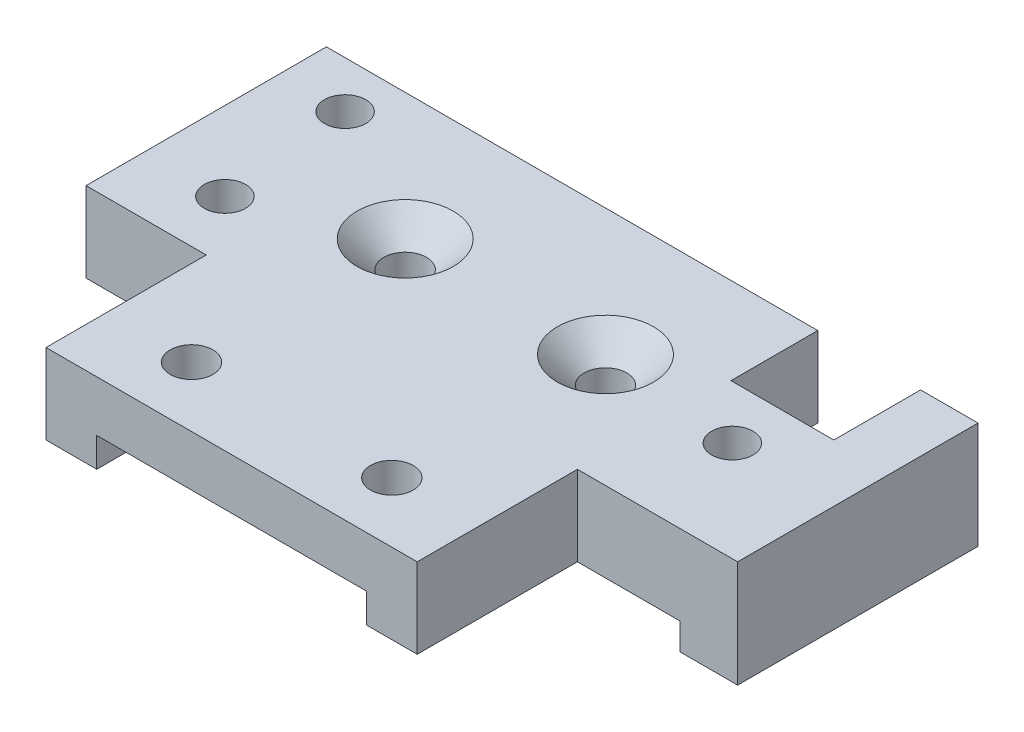
SolidWorks part; units mm, degrees
ref_plane "前视基准面" through (0, 0, 0) normal (0, 0, 1) x (1, 0, 0)
ref_plane "上视基准面" through (0, 0, 0) normal (0, 1, 0) x (1, 0, 0)
ref_plane "右视基准面" through (0, 0, 0) normal (1, 0, 0) x (0, 0, -1)
other "Configuration Table"
sketch "草图1" plane through (0, 0, 0) normal (0, 1, 0) x (1, 0, 0)
  line L1 (0, 0) -> (20.2, 0)
  line L2 (0, 0) -> (0, 25)
  line L3 (0, 25) -> (20.2, 25)
  line L4 (20.2, 0) -> (20.2, 25)
  circle A0 centre (2.6, 4.5) radius 1.6
  circle A1 centre (17.6, 4.5) radius 1.6
  circle A2 centre (17.6, 20.5) radius 1.6
  circle A3 centre (2.6, 20.5) radius 1.6
  point P7 (10.1, 0)
  point P8 (0, 12.5)
  dimension "D3" = 3.2
  dimension "D1" = 25
  dimension "D2" = 20.2
  dimension "D6" = 7.5
  dimension "D7" = 8
  dimension "D4" = 2
  dimension "D5" = 2
extrude "凸台-拉伸1" add sketch "草图1" along normal blind 3.8
sketch "草图2" plane through (20.2, 0, 0) normal (1, 0, 0) x (0, 0, -1)
  line L0 (0, 3.8) -> (25, 3.8) construction
  line L1 (25, 3.8) -> (0, 3.8)
  line L2 (25, 3.8) -> (25, -2.2)
  line L3 (25, -2.2) -> (0, -2.2)
  line L4 (0, 3.8) -> (0, -2.2)
  dimension "D1" = 6
extrude "凸台-拉伸2" add sketch "草图2" along normal blind 3.8
sketch "草图3" plane through (0, 0, 0) normal (-1, 0, 0) x (0, 0, 1)
  line L1 (-25, 3.8) -> (0, 3.8)
  line L2 (-25, 3.8) -> (-25, -2.2)
  line L3 (-25, -2.2) -> (0, -2.2)
  line L4 (0, 3.8) -> (0, -2.2)
  dimension "D1" = 6
extrude "凸台-拉伸3" add sketch "草图3" along normal blind 3.8
sketch "草图4" plane through (24, 0, 0) normal (1, 0, 0) x (0, 0, -1)
  line L0 (25, 3.8) -> (0, 3.8) construction
  line L1 (25, 3.8) -> (17, 3.8)
  line L2 (25, 3.8) -> (25, -2.2)
  line L3 (25, -2.2) -> (17, -2.2)
  line L4 (17, 3.8) -> (17, -2.2)
  line L5 (0, -2.2) -> (25, -2.2) construction
  line L6 (25, -2.2) -> (25, 3.8) construction
  dimension "D1" = 8
  dimension "D2" = 0
extrude "凸台-拉伸4" add sketch "草图4" along normal blind 12
sketch "草图5" plane through (0, 0, -25) normal (0, 0, -1) x (-1, 0, 0)
  line L0 (-36, -2.2) -> (-36, 3.8) construction
  line L1 (-36, -2.2) -> (-31.7, -2.2)
  line L2 (-36, -2.2) -> (-36, 3.8)
  line L3 (-36, 3.8) -> (-31.7, 3.8)
  line L4 (-31.7, -2.2) -> (-31.7, 3.8)
  line L5 (-36, 3.8) -> (3.8, 3.8) construction
  dimension "D1" = 4.3
extrude "凸台-拉伸5" add sketch "草图5" along normal blind 6
sketch "草图6" plane through (0, -2.2, 0) normal (0, -1, 0) x (-1, 0, 0)
  line L1 (-36, 17) -> (-31.7, 17)
  line L2 (-36, 17) -> (-36, 31)
  line L3 (-36, 31) -> (-31.7, 31)
  line L4 (-31.7, 17) -> (-31.7, 31)
extrude "凸台-拉伸6" add sketch "草图6" along normal blind 2
sketch "草图7" plane through (0, 0, -25) normal (0, 0, -1) x (-1, 0, 0)
  line L1 (3.8, 3.8) -> (0, 3.8)
  line L2 (3.8, 3.8) -> (3.8, -2.2)
  line L3 (3.8, -2.2) -> (0, -2.2)
  line L4 (0, 3.8) -> (0, -2.2)
  line L5 (-20.2, -2.2) -> (-24, -2.2)
  line L6 (-20.2, -2.2) -> (-20.2, 3.8)
  line L7 (-20.2, 3.8) -> (-24, 3.8)
  line L8 (-24, -2.2) -> (-24, 3.8)
  line L9 (-20.2, 0) -> (0, 0)
  line L10 (-20.2, 0) -> (-20.2, 3.8)
  line L11 (-20.2, 3.8) -> (0, 3.8)
  line L12 (0, 0) -> (0, 3.8)
  line M6 (-31.7, -2.2) -> (-20.2, -2.2)
  line M7 (-20.2, -2.2) -> (-20.2, 0)
  line M8 (-20.2, 0) -> (0, 0)
  line M9 (0, 0) -> (0, -2.2)
  line M10 (0, -2.2) -> (3.8, -2.2)
  line M11 (3.8, -2.2) -> (3.8, 3.8)
  line M12 (3.8, 3.8) -> (-31.7, 3.8)
extrude "凸台-拉伸7" add sketch "草图7" along normal blind 5 contours L8 L6 M6 M7 M12 | L6 L4 M8 M12 | L4 M12 M9 M10 M11
sketch "草图8" plane through (-3.8, 0, 0) normal (-1, 0, 0) x (0, 0, 1)
  line L0 (-30, -2.2) -> (-30, 3.8) construction
  line L1 (-30, 3.8) -> (-20, 3.8)
  line L2 (-30, 3.8) -> (-30, -2.2)
  line L3 (-30, -2.2) -> (-20, -2.2)
  line L4 (-20, 3.8) -> (-20, -2.2)
  line L5 (-30, -2.2) -> (0, -2.2) construction
  dimension "D1" = 0
  dimension "D2" = 10
extrude "凸台-拉伸8" add sketch "草图8" along normal blind 9
sketch "草图9" plane through (0, 3.8, 0) normal (0, 1, 0) x (1, 0, 0)
  line L0 (-3.8, 0) -> (24, 0) construction
  line L1 (-12.8, 20) -> (-3.8, 20) construction
  circle A0 centre (-7.9, 26.5) radius 1.55
  circle A1 centre (28.1, 19.5) radius 1.55
  point P6 (10.1, 0)
  dimension "D1" = 18
  dimension "D2" = 18
  dimension "D3" = 7
  dimension "D4" = 3.1
  dimension "D5" = 3.1
  dimension "D6" = 6.5
extrude "切除-拉伸1" cut sketch "草图9" against normal blind 3
sketch "草图10" plane through (0, 0.8, 0) normal (0, 1, 0) x (1, 0, 0)
  circle A0 centre (-7.9, 26.5) radius 1.05
  circle A1 centre (28.1, 19.5) radius 1.05
  dimension "D1" = 2.1
  dimension "D2" = 2.1
extrude "切除-拉伸2" cut sketch "草图10" against normal blind 3
sketch "草图11" plane through (0, 0, -20) normal (0, 0, 1) x (1, 0, 0)
  line L0 (-3.8, 3.8) -> (24, 3.8) construction
  line L1 (-3.8, 3.8) -> (-12.8, 3.8)
  line L2 (-3.8, 3.8) -> (-3.8, -2.2)
  line L3 (-3.8, -2.2) -> (-12.8, -2.2)
  line L4 (-12.8, 3.8) -> (-12.8, -2.2)
  line L5 (-3.8, -2.2) -> (-3.8, 3.8) construction
  line L6 (-12.8, -2.2) -> (-12.8, 3.8) construction
  line L7 (-12.8, -2.2) -> (-3.8, -2.2) construction
extrude "凸台-拉伸9" add sketch "草图11" along normal blind 8
sketch "草图12" plane through (0, -2.2, 0) normal (0, -1, 0) x (-1, 0, 0)
  circle A0 centre (6.9, 16.5) radius 1.05
  circle A1 centre (7.9, 26.5) radius 1.05 construction
  dimension "D1" = 2.1
  dimension "D2" = 1
  dimension "D3" = 10
extrude "切除-拉伸3" cut sketch "草图12" against normal through all
chamfer "倒角1" distance 2 angle 45 2 edges at (17.6, 3.8, -18.9) (2.6, 3.8, -18.9)
sketch "草图13" plane through (0, 3.8, 0) normal (0, 1, 0) x (1, 0, 0)
  circle A0 centre (-6.9, 16.5) radius 1.55
  dimension "D1" = 3.1
extrude "切除-拉伸4" cut sketch "草图13" against normal blind 3
sketch "草图14" plane through (0, 0, -17) normal (0, 0, 1) x (1, 0, 0)
  line L0 (24, -2.2) -> (20.2, -2.2) construction
  line L1 (24, -2.2) -> (36, -2.2)
  line L2 (24, -2.2) -> (24, 3.8)
  line L3 (24, 3.8) -> (36, 3.8)
  line L4 (36, -2.2) -> (36, 3.8)
  line L5 (31.7, -2.2) -> (24, -2.2) construction
  line L6 (36, 3.8) -> (24, 3.8) construction
  line L7 (36, 3.8) -> (36, -4.2) construction
  line L8 (36, -4.2) -> (31.7, -4.2) construction
  line L9 (31.7, -2.2) -> (36, -2.2)
  line L10 (31.7, -2.2) -> (31.7, -4.2)
  line L11 (31.7, -4.2) -> (36, -4.2)
  line L12 (36, -2.2) -> (36, -4.2)
  line M1 (24, 3.8) -> (24, -2.2)
  line M2 (24, -2.2) -> (31.7, -2.2)
  line M3 (31.7, -2.2) -> (31.7, -4.2)
  line M4 (31.7, -4.2) -> (36, -4.2)
  line M5 (36, -4.2) -> (36, 3.8)
  line M6 (36, 3.8) -> (24, 3.8)
extrude "凸台-拉伸10" add sketch "草图14" along normal blind 5 contours L1 M2 M5 M6 M1 | L1 M3 M4 M5
sketch "草图15" plane through (0, 3.8, 0) normal (0, 1, 0) x (1, 0, 0)
  line L0 (31.7, 31) -> (36, 31) construction
  line L1 (36, 31) -> (31.7, 31)
  line L2 (36, 31) -> (36, 30)
  line L3 (36, 30) -> (31.7, 30)
  line L4 (31.7, 31) -> (31.7, 30)
  line L5 (31.7, 31) -> (31.7, 25) construction
  line L6 (31.7, 25) -> (24, 25) construction
  line L7 (31.7, 25) -> (24, 25)
  line L8 (31.7, 25) -> (31.7, 23.5)
  line L9 (31.7, 23.5) -> (24, 23.5)
  line L10 (24, 25) -> (24, 23.5)
  dimension "D1" = 1
  dimension "D2" = 1.5
extrude "切除-拉伸5" cut sketch "草图15" against normal blind 10
equation "\"D6@草图1\"=15/2"
equation "\"D7@草图1\"=16/2"
